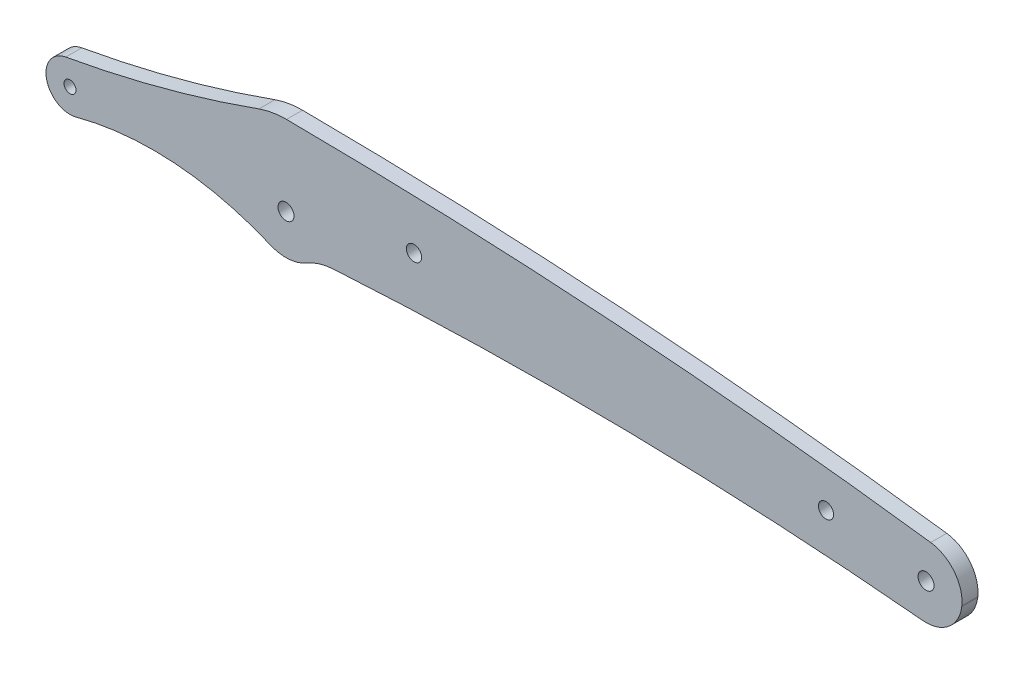
SolidWorks part; units mm, degrees
ref_plane "前视基准面" through (0, 0, 0) normal (0, 0, 1) x (1, 0, 0)
ref_plane "上视基准面" through (0, 0, 0) normal (0, 1, 0) x (1, 0, 0)
ref_plane "右视基准面" through (0, 0, 0) normal (1, 0, 0) x (0, 0, -1)
sketch "草图1" plane through (0, 0, 0) normal (0, 0, 1) x (1, 0, 0)
  line B0 (168.9539, -0.91) -> (168.9314, -1.1087)
  arc B1 (161.1738, 8.9231) -> (0.1309, 19.9996) centre (-8.3781, -1279.9726) ccw
  arc B2 (168.9539, -0.91) -> (161.1738, 8.9231) centre (160, 0) ccw
  arc B3 (159.1554, -8.9603) -> (168.9314, -1.1087) centre (160, 0) ccw
  arc B4 (159.1554, -8.9603) -> (11.798, -6.5521) centre (70, -954.7675) ccw
  arc B5 (-3.8998, -9.2082) -> (5.0868, -8.6096) centre (0, 0) ccw
  arc B6 (-3.8998, -9.2082) -> (-52.4554, -5.7978) centre (-33.1481, -78.27) ccw
  arc B7 (-55.0617, 5.9053) -> (-52.4554, -5.7978) centre (-54, 0) ccw
  arc B8 (-55.0617, 5.9053) -> (-6.7593, 18.8232) centre (-108.1481, 301.171) ccw
  arc B9 (0.1309, 19.9996) -> (-6.7593, 18.8232) centre (0, 0) ccw
  circle B10 centre (32, 7) radius 1.9
  circle B11 centre (135, 2.8) radius 1.9
  circle B12 centre (-54, 0) radius 1.5
  circle B13 centre (0, 0) radius 2
  circle B14 centre (160, 0) radius 1.5
  arc B15 (11.798, -6.5521) -> (5.0868, -8.6096) centre (12.717, -21.5239) ccw
sketch_block_instance "块1-1"
sketch_block "块1"
extrude "凸台-拉伸1" add sketch "草图1" along normal blind 4
sketch "草图2" plane through (0, 0, 4) normal (0, 0, 1) x (1, 0, 0)
  circle A0 centre (160, 0) radius 2
  dimension "D1" = 4
extrude "切除-拉伸1" cut sketch "草图2" against normal through all
